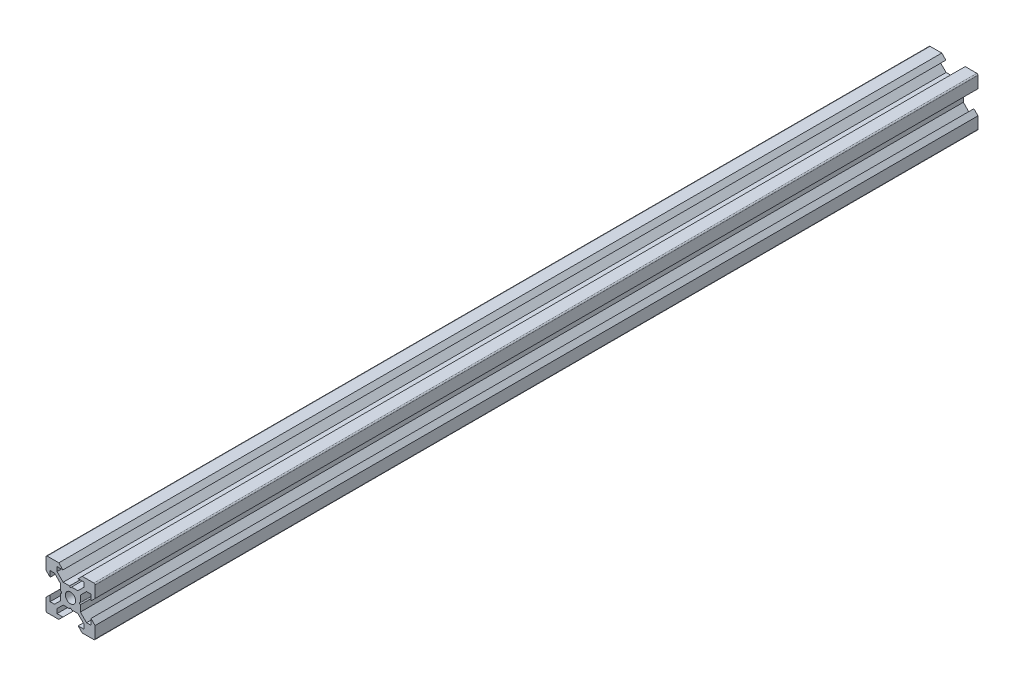
SolidWorks part; units mm, degrees
ref_plane "Front Plane" through (0, 0, 0) normal (0, 0, 1) x (1, 0, 0)
ref_plane "Top Plane" through (0, 0, 0) normal (0, 1, 0) x (1, 0, 0)
ref_plane "Right Plane" through (0, 0, 0) normal (1, 0, 0) x (0, 0, -1)
sketch "Sketch1" plane through (0, 0, 0) normal (0, 0, 1) x (1, 0, 0)
  line L0 (0, 11.7715) -> (0, -11.0375) construction
  line L1 (-10, 10) -> (10, 10) construction
  line L2 (-10, 10) -> (-10, -10) construction
  line L3 (-10, -10) -> (10, -10) construction
  line L4 (10, 10) -> (10, -10) construction
  line L5 (-10, 10) -> (10, -10) construction
  line L6 (-10, -10) -> (10, 10) construction
  line L7 (-5.5, 5.5) -> (5.5, 5.5) construction
  line L8 (-5.5, 5.5) -> (-5.5, -5.5) construction
  line L9 (-5.5, -5.5) -> (5.5, -5.5) construction
  line L10 (5.5, 5.5) -> (5.5, -5.5) construction
  line L11 (-5.5, 5.5) -> (5.5, -5.5) construction
  line L12 (-5.5, -5.5) -> (5.5, 5.5) construction
  line L13 (-10, 10) -> (-4.775, 10)
  line L14 (-4.775, 10) -> (-3.1, 8.325)
  line L15 (-3.1, 8.325) -> (-5.5, 8.325)
  line L16 (-5.5, 8.325) -> (-5.5, 6.525)
  line L17 (-5.5, 6.525) -> (-3, 4.025)
  line L18 (-3, 4.025) -> (3, 4.025)
  line L19 (-2.8044, 0) -> (3.0922, 0) construction
  line L20 (5.5, 6.525) -> (3, 4.025)
  line L21 (5.5, 8.325) -> (5.5, 6.525)
  line L22 (3.1, 8.325) -> (5.5, 8.325)
  line L23 (4.775, 10) -> (3.1, 8.325)
  line L24 (10, 10) -> (4.775, 10)
  line L25 (10, -10) -> (4.775, -10)
  line L26 (4.775, -10) -> (3.1, -8.325)
  line L27 (3.1, -8.325) -> (5.5, -8.325)
  line L28 (5.5, -8.325) -> (5.5, -6.525)
  line L29 (5.5, -6.525) -> (3, -4.025)
  line L30 (-3.1, -8.325) -> (-5.5, -8.325)
  line L31 (-3, -4.025) -> (3, -4.025)
  line L32 (-5.5, -6.525) -> (-3, -4.025)
  line L33 (-5.5, -8.325) -> (-5.5, -6.525)
  line L34 (-4.775, -10) -> (-3.1, -8.325)
  line L35 (-10, -10) -> (-4.775, -10)
  line L36 (-4.025, 3) -> (-4.025, -3)
  line L37 (-6.525, 5.5) -> (-4.025, 3)
  line L38 (-8.325, 5.5) -> (-6.525, 5.5)
  line L39 (-8.325, 3.1) -> (-8.325, 5.5)
  line L40 (-10, 4.775) -> (-8.325, 3.1)
  line L41 (-10, 10) -> (-10, 4.775)
  line L42 (-10, -10) -> (-10, -4.775)
  line L43 (-10, -4.775) -> (-8.325, -3.1)
  line L44 (-8.325, -3.1) -> (-8.325, -5.5)
  line L45 (-8.325, -5.5) -> (-6.525, -5.5)
  line L46 (-6.525, -5.5) -> (-4.025, -3)
  line L47 (10, -10) -> (10, -4.775)
  line L48 (10, -4.775) -> (8.325, -3.1)
  line L49 (8.325, -3.1) -> (8.325, -5.5)
  line L50 (8.325, -5.5) -> (6.525, -5.5)
  line L51 (6.525, -5.5) -> (4.025, -3)
  line L52 (4.025, 3) -> (4.025, -3)
  line L53 (6.525, 5.5) -> (4.025, 3)
  line L54 (8.325, 5.5) -> (6.525, 5.5)
  line L55 (8.325, 3.1) -> (8.325, 5.5)
  line L56 (10, 4.775) -> (8.325, 3.1)
  line L57 (10, 10) -> (10, 4.775)
  circle A0 centre (0, 0) radius 2.1
  point P0 (0, 0)
  point P6 (0, 0)
  point P23 (0, 4.025)
  dimension "D3" = 4.2
  dimension "D1" = 20
  dimension "D2" = 20
  dimension "D4" = 45
  dimension "D5" = 45
  dimension "D6" = 9.55
  dimension "D7" = 6.2
  dimension "D8" = 11
  dimension "D9" = 1.675
  dimension "D10" = 4.3
  dimension "D11" = 9.55
  dimension "D12" = 6.2
  dimension "D13" = 1.675
  dimension "D14" = 4.3
  dimension "D15" = 1.8
  dimension "D16" = 1.8
  dimension "D17" = 45
extrude "Boss-Extrude1" add sketch "Sketch1" along normal blind 360
fillet "Fillet1" radius 0.5 4 edges at (-10, -10, 180) (10, -10, 180) (10, 10, 180) (-10, 10, 180)
sketch "Sketch2" plane through (0, 0, 360) normal (0, 0, 1) x (1, 0, 0)
  line L0 (-0.8203, 0) -> (1.3478, 0) construction
  line L1 (0, 1.2196) -> (0, -1.1398) construction
  line L44 (-10, -4.775) -> (-10, -9.5)
  line L45 (-9.5, -10) -> (-4.775, -10)
  line L46 (-4.775, -10) -> (-3.1, -8.325)
  line L47 (-3.1, -8.325) -> (-5.5, -8.325)
  line L48 (-5.5, -8.325) -> (-5.5, -6.525)
  line L49 (-5.5, -6.525) -> (-3, -4.025)
  line L50 (-3, -4.025) -> (3, -4.025)
  line L51 (3, -4.025) -> (5.5, -6.525)
  line L52 (5.5, -6.525) -> (5.5, -8.325)
  line L53 (5.5, -8.325) -> (3.1, -8.325)
  line L54 (3.1, -8.325) -> (4.775, -10)
  line L55 (4.775, -10) -> (9.5, -10)
  line L56 (10, -9.5) -> (10, -4.775)
  line L57 (10, -4.775) -> (8.325, -3.1)
  line L58 (8.325, -3.1) -> (8.325, -5.5)
  line L59 (8.325, -5.5) -> (6.525, -5.5)
  line L60 (6.525, -5.5) -> (4.025, -3)
  line L61 (4.025, -3) -> (4.025, 3)
  line L62 (4.025, 3) -> (6.525, 5.5)
  line L63 (6.525, 5.5) -> (8.325, 5.5)
  line L64 (8.325, 5.5) -> (8.325, 3.1)
  line L65 (8.325, 3.1) -> (10, 4.775)
  line L66 (10, 4.775) -> (10, 9.5)
  line L67 (9.5, 10) -> (4.775, 10)
  line L68 (4.775, 10) -> (3.1, 8.325)
  line L69 (3.1, 8.325) -> (5.5, 8.325)
  line L70 (5.5, 8.325) -> (5.5, 6.525)
  line L71 (5.5, 6.525) -> (3, 4.025)
  line L72 (3, 4.025) -> (-3, 4.025)
  line L73 (-3, 4.025) -> (-5.5, 6.525)
  line L74 (-5.5, 6.525) -> (-5.5, 8.325)
  line L75 (-5.5, 8.325) -> (-3.1, 8.325)
  line L76 (-3.1, 8.325) -> (-4.775, 10)
  line L77 (-4.775, 10) -> (-9.5, 10)
  line L78 (-10, 9.5) -> (-10, 4.775)
  line L79 (-10, 4.775) -> (-8.325, 3.1)
  line L80 (-8.325, 3.1) -> (-8.325, 5.5)
  line L81 (-8.325, 5.5) -> (-6.525, 5.5)
  line L82 (-6.525, 5.5) -> (-4.025, 3)
  line L83 (-4.025, 3) -> (-4.025, -3)
  line L84 (-4.025, -3) -> (-6.525, -5.5)
  line L85 (-6.525, -5.5) -> (-8.325, -5.5)
  line L86 (-8.325, -5.5) -> (-8.325, -3.1)
  line L87 (-8.325, -3.1) -> (-10, -4.775)
  line L88 (-10, -4.775) -> (-10, -9.5)
  line L89 (-9.5, -10) -> (-4.775, -10)
  line L90 (-4.775, -10) -> (-3.1, -8.325)
  line L91 (-3.1, -8.325) -> (-5.5, -8.325)
  line L92 (-5.5, -8.325) -> (-5.5, -6.525)
  line L93 (-5.5, -6.525) -> (-3, -4.025)
  line L94 (-3, -4.025) -> (3, -4.025)
  line L95 (3, -4.025) -> (5.5, -6.525)
  line L96 (5.5, -6.525) -> (5.5, -8.325)
  line L97 (5.5, -8.325) -> (3.1, -8.325)
  line L98 (3.1, -8.325) -> (4.775, -10)
  line L99 (4.775, -10) -> (9.5, -10)
  line L100 (10, -9.5) -> (10, -4.775)
  line L101 (10, -4.775) -> (8.325, -3.1)
  line L102 (8.325, -3.1) -> (8.325, -5.5)
  line L103 (8.325, -5.5) -> (6.525, -5.5)
  line L104 (6.525, -5.5) -> (4.025, -3)
  line L105 (4.025, -3) -> (4.025, 3)
  line L106 (4.025, 3) -> (6.525, 5.5)
  line L107 (6.525, 5.5) -> (8.325, 5.5)
  line L108 (8.325, 5.5) -> (8.325, 3.1)
  line L109 (8.325, 3.1) -> (10, 4.775)
  line L110 (10, 4.775) -> (10, 9.5)
  line L111 (9.5, 10) -> (4.775, 10)
  line L112 (4.775, 10) -> (3.1, 8.325)
  line L113 (3.1, 8.325) -> (5.5, 8.325)
  line L114 (5.5, 8.325) -> (5.5, 6.525)
  line L115 (5.5, 6.525) -> (3, 4.025)
  line L116 (3, 4.025) -> (-3, 4.025)
  line L117 (-3, 4.025) -> (-5.5, 6.525)
  line L118 (-5.5, 6.525) -> (-5.5, 8.325)
  line L119 (-5.5, 8.325) -> (-3.1, 8.325)
  line L120 (-3.1, 8.325) -> (-4.775, 10)
  line L121 (-4.775, 10) -> (-9.5, 10)
  line L122 (-10, 9.5) -> (-10, 4.775)
  line L123 (-10, 4.775) -> (-8.325, 3.1)
  line L124 (-8.325, 3.1) -> (-8.325, 5.5)
  line L125 (-8.325, 5.5) -> (-6.525, 5.5)
  line L126 (-6.525, 5.5) -> (-4.025, 3)
  line L127 (-4.025, 3) -> (-4.025, -3)
  line L128 (-4.025, -3) -> (-6.525, -5.5)
  line L129 (-6.525, -5.5) -> (-8.325, -5.5)
  line L130 (-8.325, -5.5) -> (-8.325, -3.1)
  line L131 (-8.325, -3.1) -> (-10, -4.775)
  circle A0 centre (-4.025, 0) radius 0.4
  circle A1 centre (4.025, 0) radius 0.4
  circle A2 centre (0, 4.025) radius 0.4
  circle A3 centre (0, -4.025) radius 0.4
  arc A4 (-10, -9.5) -> (-9.5, -10) centre (-9.5, -9.5) ccw
  arc A5 (9.5, -10) -> (10, -9.5) centre (9.5, -9.5) ccw
  arc A6 (10, 9.5) -> (9.5, 10) centre (9.5, 9.5) ccw
  arc A7 (-9.5, 10) -> (-10, 9.5) centre (-9.5, 9.5) ccw
  arc A8 (-10, -9.5) -> (-9.5, -10) centre (-9.5, -9.5) ccw
  arc A9 (9.5, -10) -> (10, -9.5) centre (9.5, -9.5) ccw
  arc A10 (10, 9.5) -> (9.5, 10) centre (9.5, 9.5) ccw
  arc A11 (-9.5, 10) -> (-10, 9.5) centre (-9.5, 9.5) ccw
  dimension "D2" = 0.8
  dimension "D3" = 0.8
  dimension "D1" = 0
extrude "Cut-Extrude1" cut sketch "Sketch2" against normal through all contours L127 A0 | L116 A2 | A1 L105 | A3 L94
